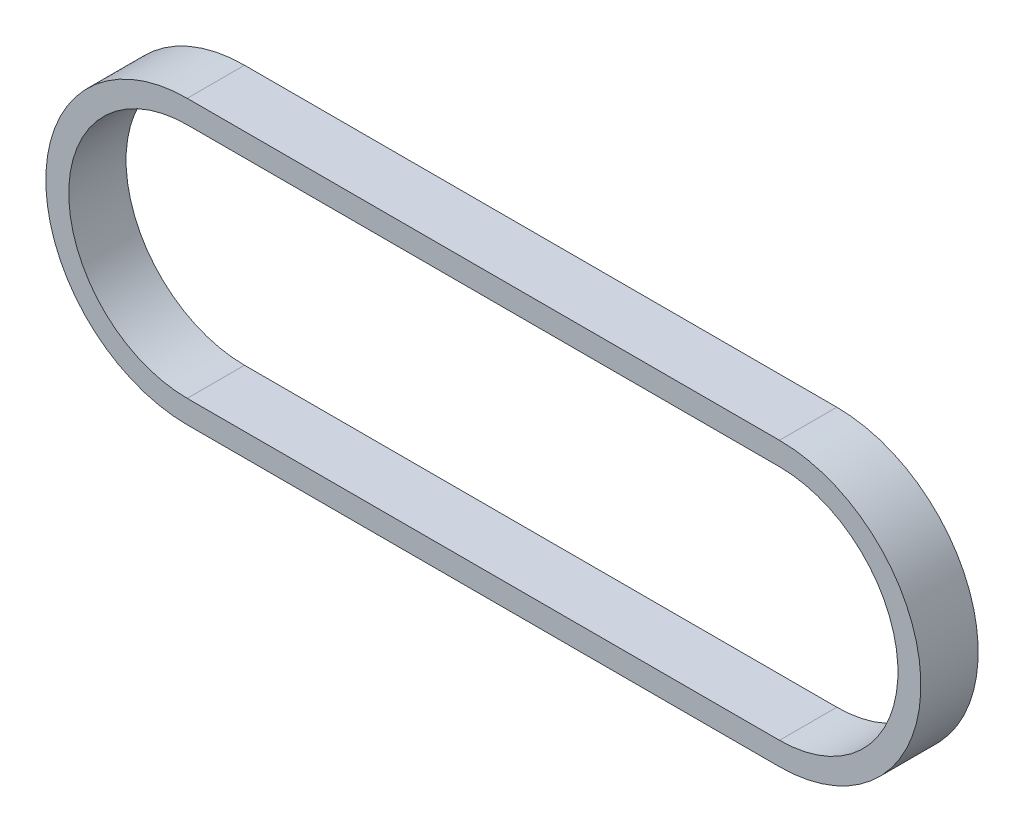
SolidWorks part; units mm, degrees
ref_plane "Plan de face" through (0, 0, 0) normal (0, 0, 1) x (1, 0, 0)
ref_plane "Plan de dessus" through (0, 0, 0) normal (0, 1, 0) x (1, 0, 0)
ref_plane "Plan de droite" through (0, 0, 0) normal (1, 0, 0) x (0, 0, -1)
sketch "Esquisse1" plane through (0, 0, 0) normal (0, 0, 1) x (1, 0, 0)
  line L0 (0, 0) -> (62, 0) construction
  line L1 (0, 12.4) -> (62, 12.4)
  line L2 (0, -12.4) -> (62, -12.4)
  line L3 (0, 0) -> (62, 0) construction
  line L4 (0, 14.8) -> (62, 14.8)
  line L5 (0, -14.8) -> (62, -14.8)
  arc A0 (0, 12.4) -> (0, -12.4) centre (0, 0) ccw
  arc A1 (62, -12.4) -> (62, 12.4) centre (62, 0) ccw
  arc A2 (0, 14.8) -> (0, -14.8) centre (0, 0) ccw
  arc A3 (62, -14.8) -> (62, 14.8) centre (62, 0) ccw
  point P3 (31, 0)
  point P10 (31, 0)
  dimension "D3" = 12.4
  dimension "D1" = 62
  dimension "D2" = 2.4
extrude "Boss.-Extru.1" add sketch "Esquisse1" along normal blind 6
